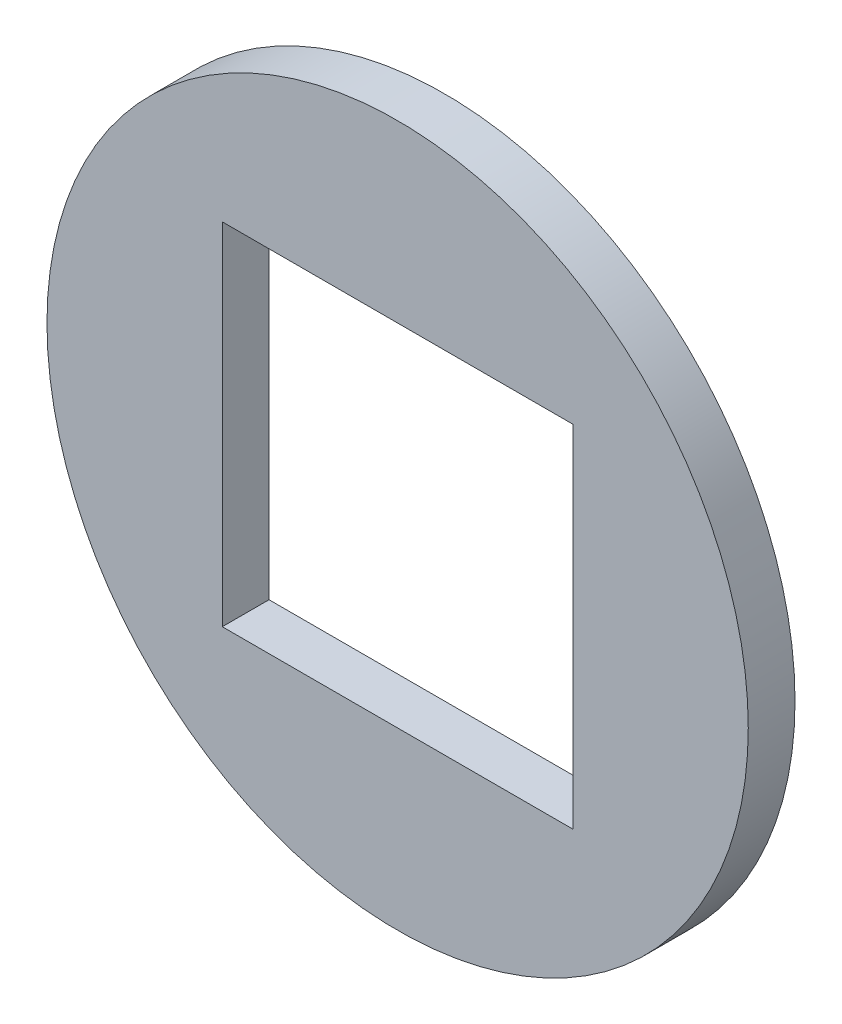
SolidWorks part; units mm, degrees
ref_plane "Front Plane" through (0, 0, 0) normal (0, 0, 1) x (1, 0, 0)
ref_plane "Top Plane" through (0, 0, 0) normal (0, 1, 0) x (1, 0, 0)
ref_plane "Right Plane" through (0, 0, 0) normal (1, 0, 0) x (0, 0, -1)
sketch "Sketch1" plane through (0, 0, 0) normal (0, 0, 1) x (1, 0, 0)
  line L1 (-7.5, 7.5) -> (7.5, 7.5)
  line L2 (-7.5, 7.5) -> (-7.5, -7.5)
  line L3 (-7.5, -7.5) -> (7.5, -7.5)
  line L4 (7.5, 7.5) -> (7.5, -7.5)
  line L5 (-7.5, 7.5) -> (7.5, -7.5) construction
  line L6 (-7.5, -7.5) -> (7.5, 7.5) construction
  circle A0 centre (0, 0) radius 15
  dimension "D1" = 30
  dimension "D2" = 15
  dimension "D3" = 15
extrude "Boss-Extrude1" add sketch "Sketch1" along normal blind 2
